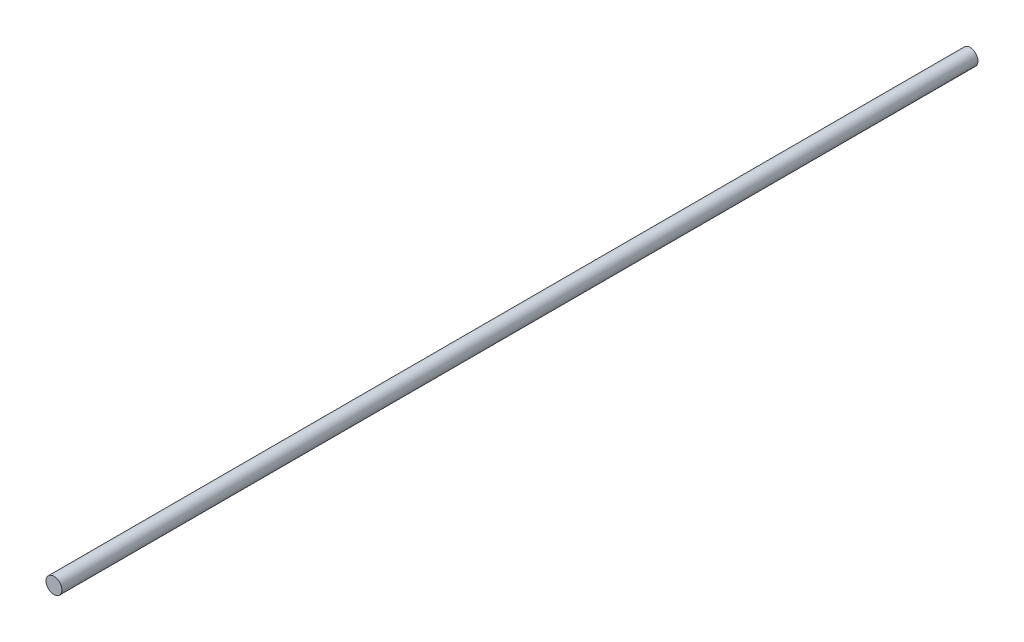
SolidWorks part; units mm, degrees
material "6063-O, Barra estrusa (SS)"
ref_plane "Piano frontale" through (0, 0, 0) normal (0, 0, 1) x (1, 0, 0)
ref_plane "Piano superiore" through (0, 0, 0) normal (0, 1, 0) x (1, 0, 0)
ref_plane "Piano destro" through (0, 0, 0) normal (1, 0, 0) x (0, 0, -1)
sketch "Schizzo1" plane through (0, 0, 0) normal (0, 0, 1) x (1, 0, 0)
  circle A0 centre (0, 0) radius 1.5
  dimension "D1" = 3
extrude "Estrusione-Estrusione1" add sketch "Schizzo1" along normal blind 173
